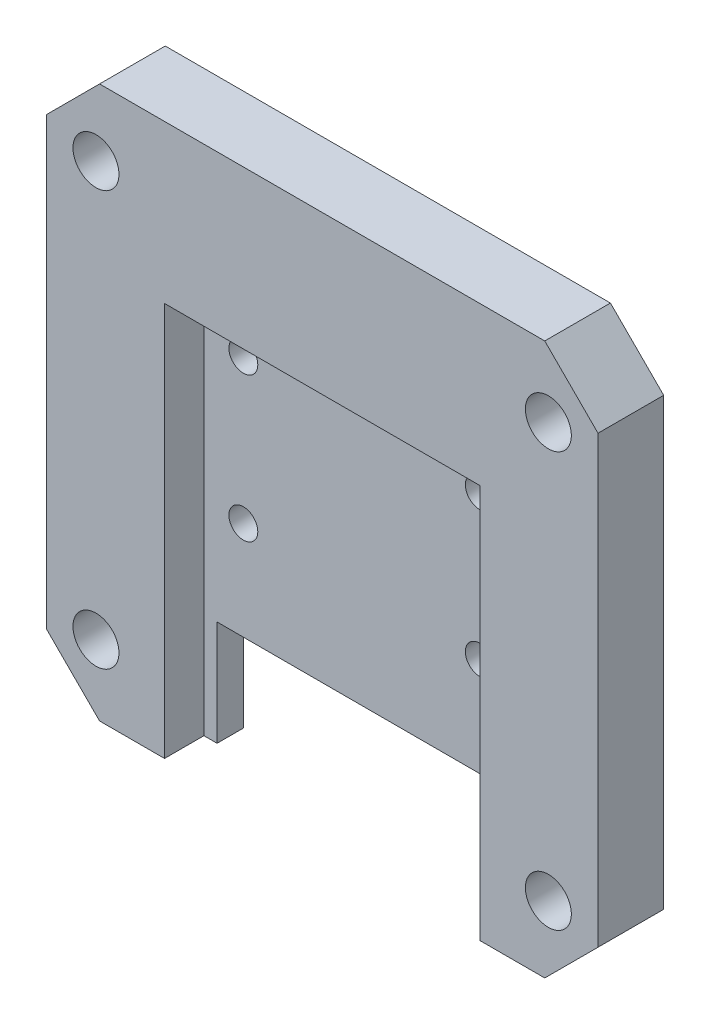
SolidWorks part; units mm, degrees
ref_plane "Front Plane" through (0, 0, 0) normal (0, 0, 1) x (1, 0, 0)
ref_plane "Top Plane" through (0, 0, 0) normal (0, 1, 0) x (1, 0, 0)
ref_plane "Right Plane" through (0, 0, 0) normal (1, 0, 0) x (0, 0, -1)
sketch "Sketch1" plane through (0, 0, 0) normal (0, 0, 1) x (1, 0, 0)
  line L0 (4.055, 42) -> (0, 37.945)
  line L1 (4.055, 0) -> (37.945, 0)
  line L2 (0, 4.055) -> (0, 37.945)
  line L3 (4.055, 42) -> (37.945, 42)
  line L4 (42, 4.055) -> (42, 37.945)
  line L5 (37.945, 42) -> (42, 37.945)
  line L6 (42, 4.055) -> (37.945, 0)
  line L7 (0, 4.055) -> (4.055, 0)
  line L8 (21, 42) -> (21, 0) construction
  line L9 (0, 21) -> (42, 21) construction
  line L11 (7, 7) -> (35, 7) construction
  line L12 (7, 7) -> (7, 35) construction
  line L13 (7, 35) -> (35, 35) construction
  line L14 (35, 7) -> (35, 35) construction
  line L15 (7, 7) -> (35, 35) construction
  line L16 (7, 35) -> (35, 7) construction
  circle A0 centre (3.7797, 36.775) radius 1.75
  circle A1 centre (3.7797, 5.225) radius 1.75
  circle A2 centre (38.2203, 5.225) radius 1.75
  circle A3 centre (38.2203, 36.775) radius 1.75
  point P4 (21, 21)
  dimension "D14" = 3.5
  dimension "D18" = 3.5
  dimension "D1" = 42
  dimension "D2" = 42
  dimension "D3" = 33.89
  dimension "D4" = 33.89
  dimension "D5" = 16.945
  dimension "D6" = 16.945
  dimension "D7" = 16.945
  dimension "D8" = 16.945
  dimension "D9" = 135
  dimension "D10" = 135
  dimension "D11" = 3.5
  dimension "D12" = 28
  dimension "D13" = 28
  dimension "D15" = 1.775
  dimension "D16" = 3.5
  dimension "D17" = 1.775
extrude "Boss-Extrude1" add sketch "Sketch1" along normal blind 5
sketch "Sketch2" plane through (0, 0, 5) normal (0, 0, 1) x (1, 0, 0)
  line L0 (4.055, 0) -> (37.945, 0) construction
  line L1 (10, 8) -> (32, 8)
  line L2 (10, 8) -> (10, 0)
  line L3 (10, 0) -> (32, 0)
  line L4 (32, 8) -> (32, 0)
  line L5 (0, 37.945) -> (0, 4.055) construction
  dimension "D1" = 22
  dimension "D2" = 8
  dimension "D3" = 10
extrude "Cut-Extrude1" cut sketch "Sketch2" against normal through all both and the other way through all
sketch "Sketch3" plane through (0, 0, 5) normal (0, 0, 1) x (1, 0, 0)
  line L0 (4.055, 0) -> (10, 0) construction
  line L1 (9, 0) -> (33, 0)
  line L2 (9, 0) -> (9, 30)
  line L3 (9, 30) -> (33, 30)
  line L4 (33, 0) -> (33, 30)
  line L5 (0, 37.945) -> (0, 4.055) construction
  dimension "D1" = 24
  dimension "D2" = 30
  dimension "D3" = 9
extrude "Cut-Extrude2" cut sketch "Sketch3" against normal blind 3
sketch "Sketch4" plane through (0, 0, 2) normal (0, 0, 1) x (1, 0, 0)
  line L0 (33, 30) -> (9, 30) construction
  line L1 (9, 30) -> (9, 0) construction
  circle A0 centre (12, 26.5) radius 1.1
  circle A1 centre (30, 26.5) radius 1.1
  circle A2 centre (12, 15.5) radius 1.1
  circle A3 centre (30, 15.5) radius 1.1
  dimension "D1" = 3.5
  dimension "D2" = 2.2
  dimension "D3" = 2.2
  dimension "D4" = 2.2
  dimension "D5" = 2.2
  dimension "D6" = 18
  dimension "D7" = 3
  dimension "D8" = 11
extrude "Cut-Extrude3" cut sketch "Sketch4" against normal blind 3
